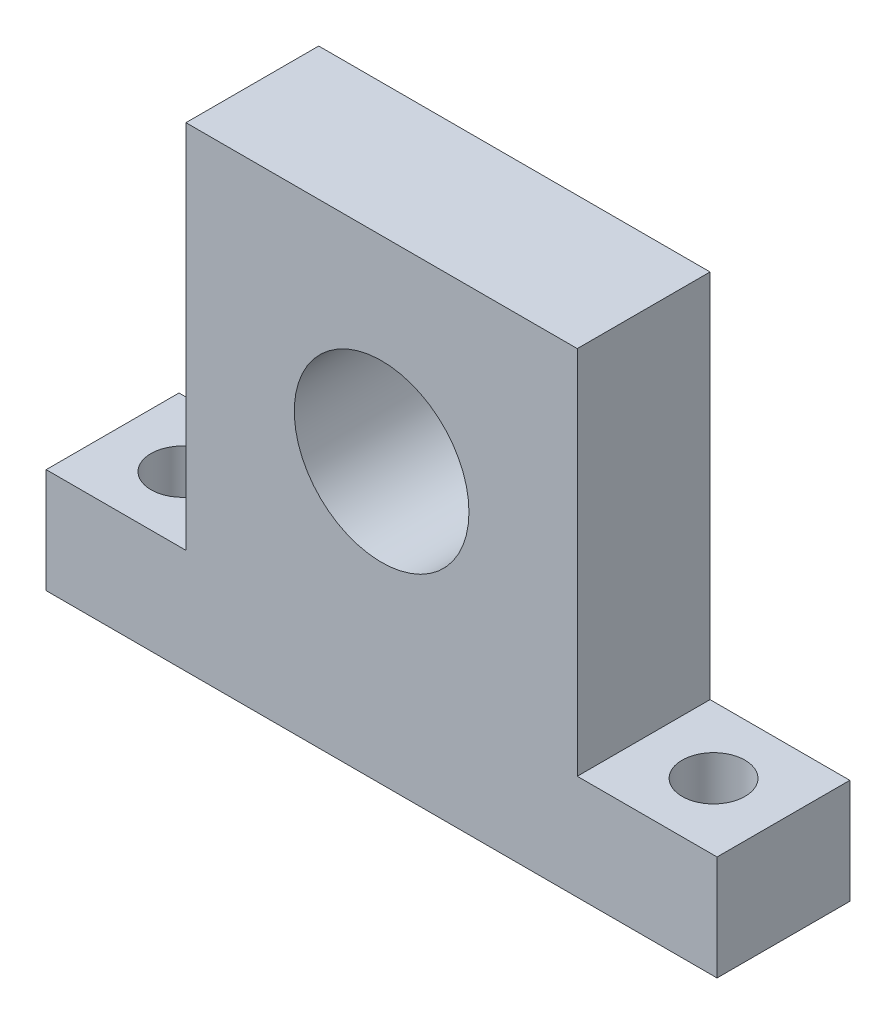
SolidWorks part; units mm, degrees
ref_plane "前视基准面" through (0, 0, 0) normal (0, 0, 1) x (1, 0, 0)
ref_plane "上视基准面" through (0, 0, 0) normal (0, 1, 0) x (1, 0, 0)
ref_plane "右视基准面" through (0, 0, 0) normal (1, 0, 0) x (0, 0, -1)
other "Configuration Table"
sketch "草图1" plane through (0, 0, 0) normal (0, 0, 1) x (1, 0, 0)
  line L0 (0, 0) -> (0, 83.6782) construction
  line L1 (-48, -40) -> (-48, -25)
  line L2 (-48, -25) -> (-28, -25)
  line L3 (-28, -25) -> (-28, 28)
  line L4 (-28, 28) -> (28, 28)
  line L5 (-48, -40) -> (48, -40)
  line L6 (48, -40) -> (48, -25)
  line L7 (48, -25) -> (28, -25)
  line L8 (28, -25) -> (28, 28)
  circle A0 centre (0, 0) radius 12.5
  dimension "D6" = 25
  dimension "D1" = 40
  dimension "D2" = 68
  dimension "D3" = 96
  dimension "D4" = 56
  dimension "D5" = 15
extrude "凸台-拉伸1" add sketch "草图1" along normal blind 19
sketch "草图2" plane through (0, -25, 0) normal (0, 1, 0) x (1, 0, 0)
  line L0 (0, 0) -> (0, -35.8722) construction
  line L1 (28, 0) -> (-28, 0) construction
  line L2 (-48, -19) -> (-48, 0) construction
  circle A0 centre (-38, -9.5) radius 4.5
  circle A1 centre (38, -9.5) radius 4.5
  point P10 (-48, -9.5)
  point P11 (-38, -9.5)
  dimension "D1" = 76
  dimension "D2" = 9
extrude "切除-拉伸1" cut sketch "草图2" against normal through all
